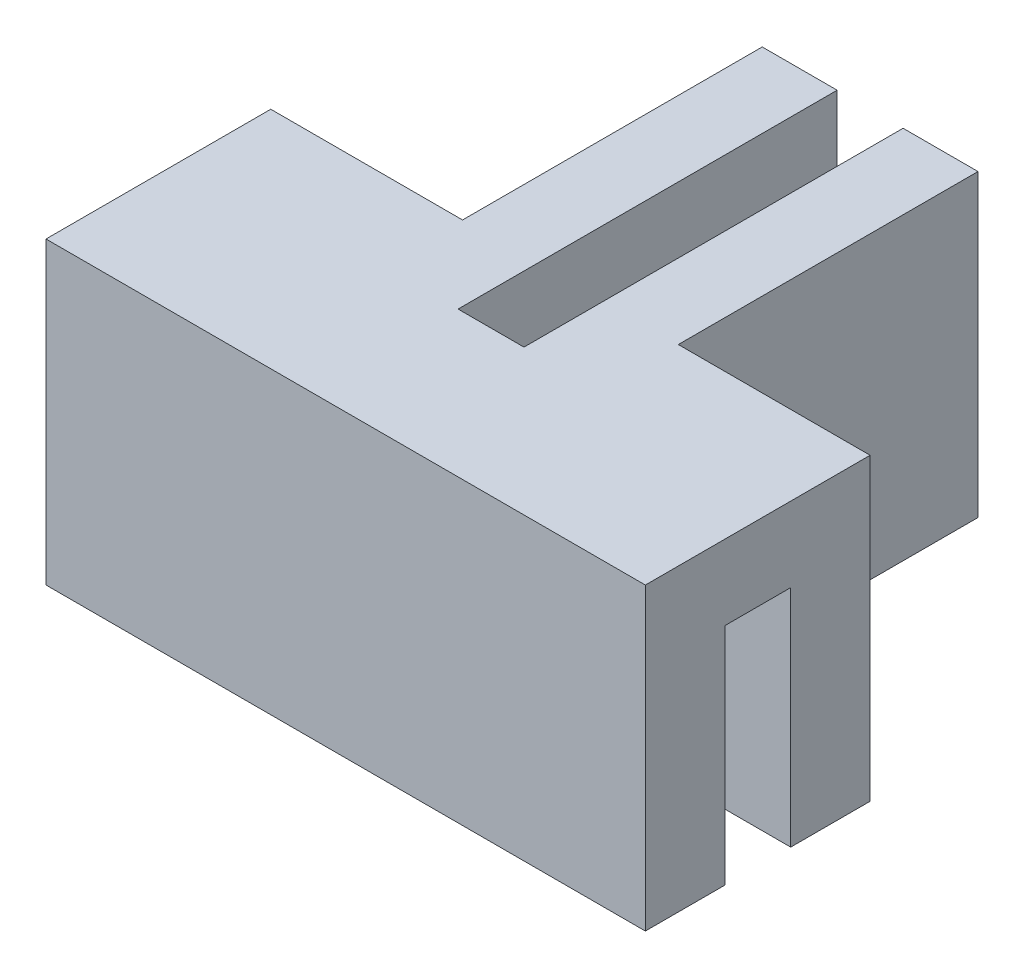
SolidWorks part; units mm, degrees
ref_plane "Front Plane" through (0, 0, 0) normal (0, 0, 1) x (1, 0, 0)
ref_plane "Top Plane" through (0, 0, 0) normal (0, 1, 0) x (1, 0, 0)
ref_plane "Right Plane" through (0, 0, 0) normal (1, 0, 0) x (0, 0, -1)
sketch "Sketch2" plane through (0, 0, 0) normal (0, 1, 0) x (1, 0, 0)
  line L0 (-1.397, 6.35) -> (1.397, 6.35) construction
  line L1 (-12.7, 0) -> (12.7, 0)
  line L2 (-12.7, 0) -> (-12.7, -9.525)
  line L3 (-12.7, -9.525) -> (12.7, -9.525)
  line L4 (12.7, 0) -> (12.7, -9.525)
  line L5 (-4.572, 0) -> (-1.397, 0)
  line L6 (-4.572, 0) -> (-4.572, 12.7)
  line L7 (-4.572, 12.7) -> (-1.397, 12.7)
  line L8 (-1.397, 0) -> (-1.397, 12.7)
  line L9 (4.572, 0) -> (1.397, 0)
  line L10 (4.572, 0) -> (4.572, 12.7)
  line L11 (4.572, 12.7) -> (1.397, 12.7)
  line L12 (1.397, 0) -> (1.397, 12.7)
  line L13 (-12.7, -3.3655) -> (12.7, -3.3655) construction
  line L14 (-1.397, 0) -> (1.397, 0)
  line L15 (-1.397, 0) -> (-1.397, -3.3655)
  line L16 (-1.397, -3.3655) -> (1.397, -3.3655)
  line L17 (1.397, 0) -> (1.397, -3.3655)
  line L18 (-12.7, -6.1595) -> (12.7, -6.1595) construction
  line L19 (-12.7, -6.1595) -> (-12.7, -3.3655) construction
  point P13 (0, 0)
  point P17 (0, 6.35)
  point P24 (-12.7, -4.7625)
  point P25 (-12.7, -4.7625)
  point P26 (-1.397, -3.3655)
  dimension "D1" = 2.794
  dimension "D2" = 9.525
  dimension "D3" = 25.4
  dimension "D4" = 3.175
  dimension "D5" = 12.7
  dimension "D6" = 2.794
extrude "Boss-Extrude1" add sketch "Sketch2" along normal blind 12.7 contours L4 L1 L2 L3 | L1 L8 L7 L6 | L12 L1 L10 L11
sketch "Sketch3" plane through (0, 0, 0) normal (0, -1, 0) x (1, 0, 0)
  line L0 (-12.7, 0) -> (-12.7, 9.525) construction
  line L1 (-12.7, 6.1595) -> (12.7, 6.1595)
  line L2 (-12.7, 6.1595) -> (-12.7, 3.3655)
  line L3 (-12.7, 3.3655) -> (12.7, 3.3655)
  line L4 (12.7, 6.1595) -> (12.7, 3.3655)
  line L5 (12.7, 0) -> (12.7, 9.525) construction
  point P8 (-12.7, 6.2487)
  point P9 (-12.7, 2.4118)
  point P10 (-12.7, 6.78)
  point P11 (-12.7, -4.4652)
  point P12 (-12.7, 4.7625)
  point P13 (-12.7, 4.7625)
  dimension "D1" = 2.794
extrude "Cut-Extrude1" cut sketch "Sketch3" against normal blind 9.525
